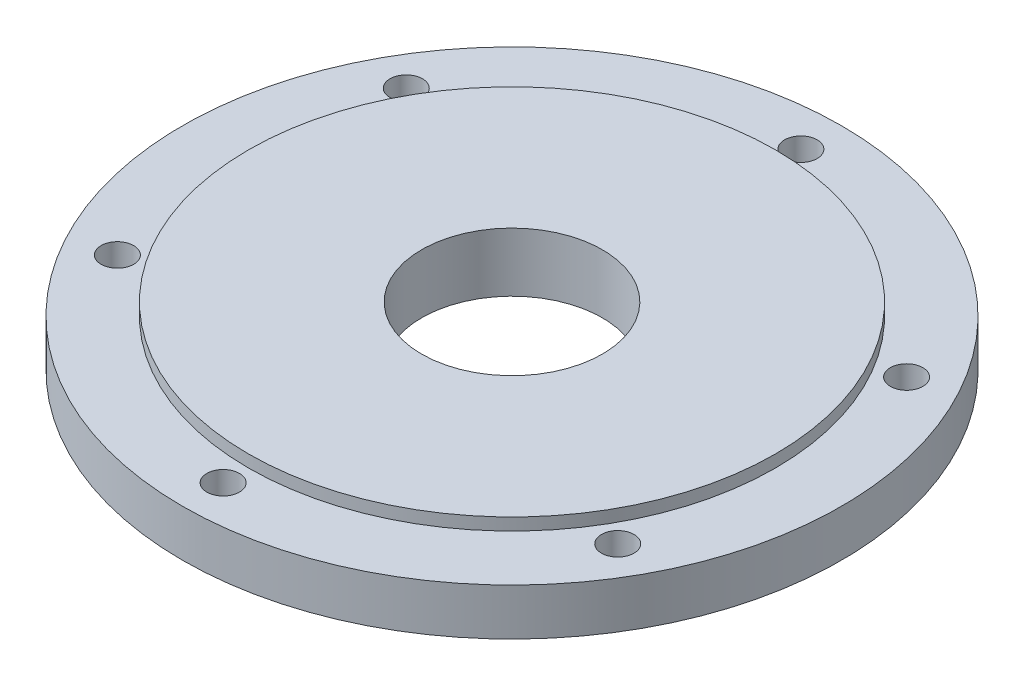
SolidWorks part; units mm, degrees
ref_plane "Front Plane" through (0, 0, 0) normal (0, 0, 1) x (1, 0, 0)
ref_plane "Top Plane" through (0, 0, 0) normal (0, 1, 0) x (1, 0, 0)
ref_plane "Right Plane" through (0, 0, 0) normal (1, 0, 0) x (0, 0, -1)
sketch "Sketch1" plane through (0, 0, 0) normal (0, 1, 0) x (1, 0, 0)
  line L0 (0, 81) -> (0, 0) construction
  line L1 (0, 0) -> (81, 0) construction
  circle A0 centre (0, 0) radius 22.225
  circle A1 centre (0, 0) radius 81
  circle A2 centre (0, 0) radius 71 construction
  circle A3 centre (0, 71) radius 4
  circle A4 centre (61.4878, 35.5) radius 4
  circle A5 centre (61.4878, -35.5) radius 4
  circle A6 centre (0, -71) radius 4
  circle A7 centre (-61.4878, -35.5) radius 4
  circle A8 centre (-61.4878, 35.5) radius 4
  point P21 (0, 0)
  dimension "D1" = 162
  dimension "D2" = 44.45
  dimension "D3" = 142
  dimension "D4" = 8
  dimension "D5" = 6
extrude "Boss-Extrude1" add sketch "Sketch1" against normal blind 14.5
sketch "Sketch2" plane through (0, 0, 0) normal (0, 1, 0) x (1, 0, 0)
  circle A0 centre (0, 0) radius 64.75
  circle A1 centre (0, 0) radius 87.4988
  dimension "D1" = 129.5
extrude "Cut-Extrude1" cut sketch "Sketch2" against normal blind 3
